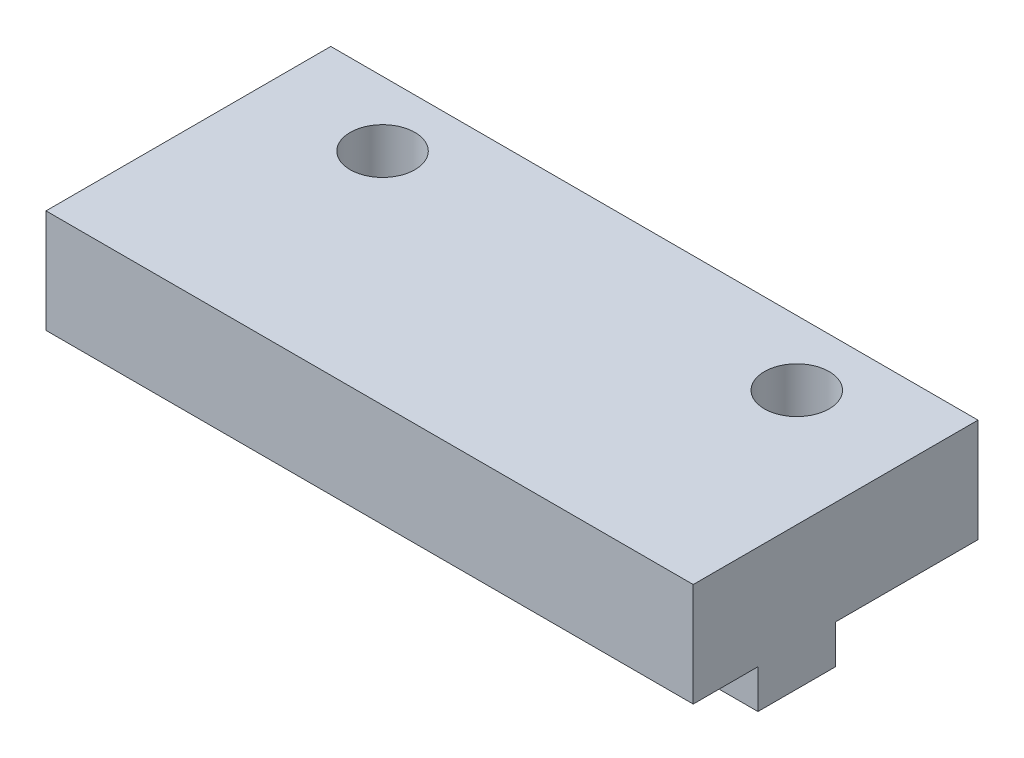
SolidWorks part; units mm, degrees
ref_plane "Front Plane" through (0, 0, 0) normal (0, 0, 1) x (1, 0, 0)
ref_plane "Top Plane" through (0, 0, 0) normal (0, 1, 0) x (1, 0, 0)
ref_plane "Right Plane" through (0, 0, 0) normal (1, 0, 0) x (0, 0, -1)
sketch "Sketch1" plane through (0, 0, 0) normal (0, 1, 0) x (1, 0, 0)
  line L0 (0, 0) -> (25, 0)
  line L1 (0, 0) -> (0, 5)
  line L2 (25, 0) -> (25, 5)
  line L3 (0, 5) -> (25, 5)
  line L4 (0, 2.5) -> (25, 2.5) construction
  line L5 (12.5, 5) -> (12.5, 0) construction
  circle A0 centre (4.5, 2.5) radius 1.25
  circle A1 centre (20.5, 2.5) radius 1.25
  dimension "D3" = 16
  dimension "D5" = 2.5
  dimension "D6" = 2.5
  dimension "D1" = 25
  dimension "D2" = 5
  dimension "D4" = 8
extrude "Boss-Extrude1" add sketch "Sketch1" along normal blind 4
sketch "Sketch2" plane through (0, 0, 0) normal (0, 0, 1) x (1, 0, 0)
  line L4 (0, 0) -> (25, 0)
  line L5 (25, 0) -> (25, 4)
  line L6 (25, 4) -> (0, 4)
  line L7 (0, 4) -> (0, 0)
  line L8 (0, 0) -> (25, 0)
  line L9 (25, 0) -> (25, 4)
  line L10 (25, 4) -> (0, 4)
  line L11 (0, 4) -> (0, 0)
  dimension "D1" = 0
extrude "Boss-Extrude2" add sketch "Sketch2" along normal blind 6
sketch "Sketch3" plane through (0, 0, 0) normal (0, -1, 0) x (1, 0, 0)
  line L0 (25, 3.5) -> (25, 0.5)
  line L1 (25, 3.5) -> (0, 3.5)
  line L2 (25, 0.5) -> (0, 0.5)
  line L3 (0, 3.5) -> (0, 0.5)
  line L4 (25, 6) -> (25, -5) construction
  line L5 (0, -5) -> (0, 6) construction
  line L6 (0, 6) -> (25, 6) construction
  dimension "D1" = 3
  dimension "D2" = 2.5
extrude "Boss-Extrude3" add sketch "Sketch3" along normal blind 1.5
